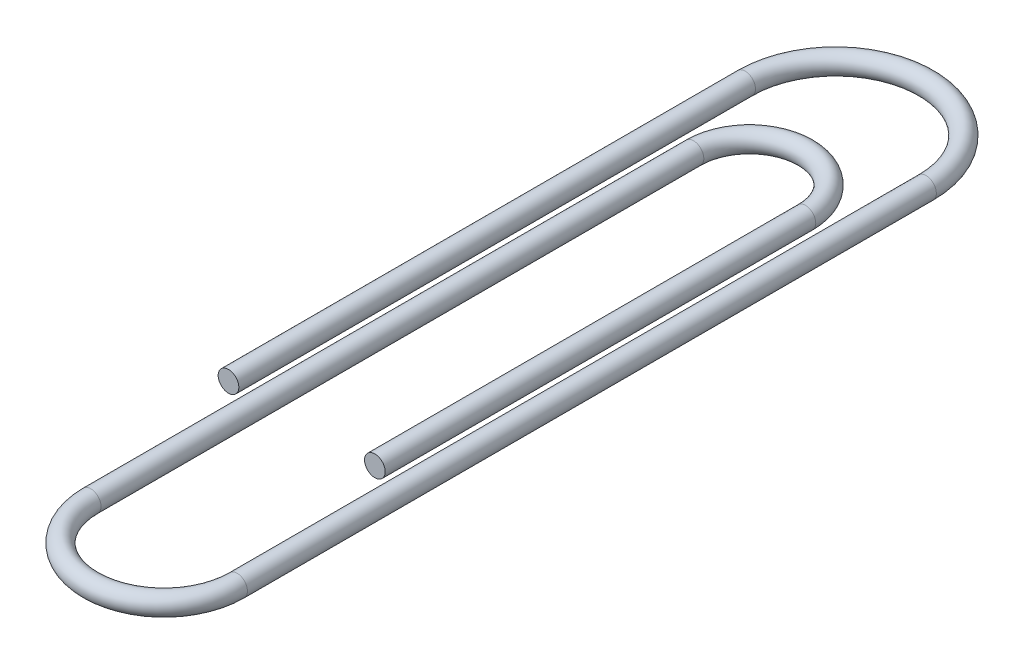
SolidWorks part; units mm, degrees
material "Plain Carbon Steel"
ref_plane "Front Plane" through (0, 0, 0) normal (0, 0, 1) x (1, 0, 0)
ref_plane "Top Plane" through (0, 0, 0) normal (0, 1, 0) x (1, 0, 0)
ref_plane "Right Plane" through (0, 0, 0) normal (1, 0, 0) x (0, 0, -1)
sketch "Sketch1" plane through (0, 0, 0) normal (0, 1, 0) x (1, 0, 0)
  line L0 (0, 0) -> (0, 25)
  line L1 (-8.5, 30) -> (2, 30) construction
  line L2 (-6.5, 25) -> (-6.5, -10)
  line L3 (-6.5, 25) -> (0, 25) construction
  line L4 (2, -10) -> (2, 30)
  line L5 (-6.5, -10) -> (2, -10) construction
  line L6 (-8.5, 30) -> (-8.5, 0)
  arc A0 (0, 25) -> (-6.5, 25) centre (-3.25, 25) ccw
  arc A1 (-6.5, -10) -> (2, -10) centre (-2.25, -10) ccw
  arc A2 (2, 30) -> (-8.5, 30) centre (-3.25, 30) ccw
  dimension "D1" = 25
  dimension "D2" = 35
  dimension "D3" = 40
  dimension "D4" = 30
  dimension "D5" = 10.5
  dimension "D6" = 6.5
  dimension "D7" = 8.5
sweep "Sweep1" add path "Sketch1" circular profile diameter 1.2 parameters "D3"=1.2
